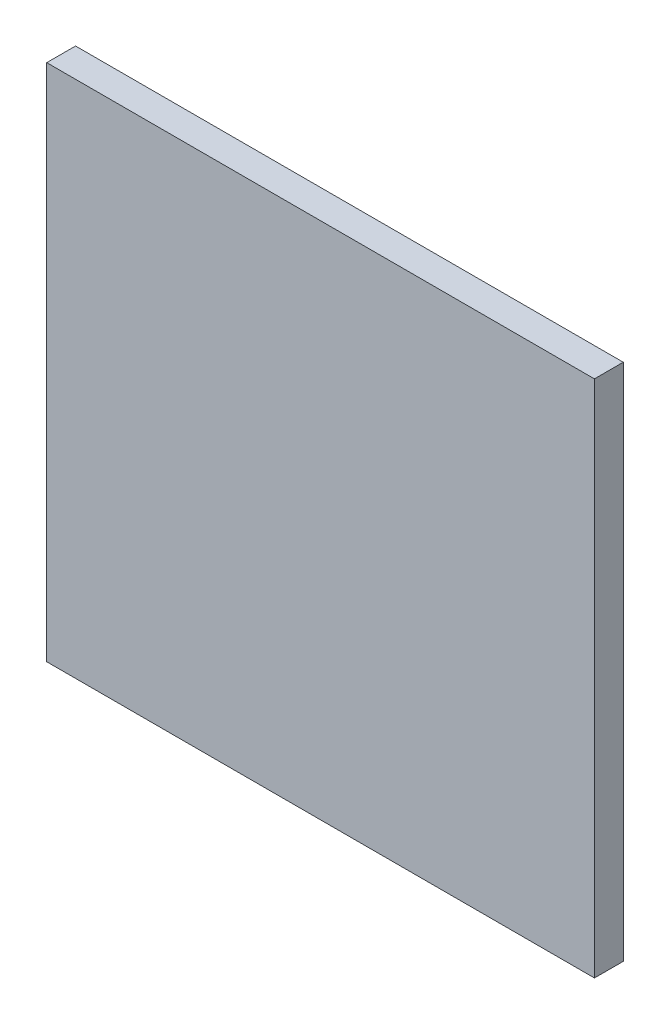
SolidWorks part; units mm, degrees
ref_plane "Спереди" through (0, 0, 0) normal (0, 0, 1) x (1, 0, 0)
ref_plane "Сверху" through (0, 0, 0) normal (0, 1, 0) x (1, 0, 0)
ref_plane "Справа" through (0, 0, 0) normal (1, 0, 0) x (0, 0, -1)
sketch "Эскиз1" plane through (0, 0, 0) normal (0, 0, 1) x (1, 0, 0)
  line L1 (0, 0) -> (3.8, 0)
  line L2 (0, 0) -> (0, -3.6)
  line L3 (0, -3.6) -> (3.8, -3.6)
  line L4 (3.8, 0) -> (3.8, -3.6)
  dimension "D1" = 3.8
  dimension "D2" = 3.6
extrude "Бобышка-Вытянуть1" add sketch "Эскиз1" along normal blind 0.2
sketch "Эскиз2" plane through (0, 0, 0) normal (0, 0, -1) x (-1, 0, 0)
  line L0 (-3.8, -1.8) -> (0, -1.8) construction
  line L1 (-0.65, -1.5) -> (-0.15, -1.5)
  line L2 (-0.65, -1.5) -> (-0.65, -2.1)
  line L3 (-0.65, -2.1) -> (-0.15, -2.1)
  line L4 (-0.15, -1.5) -> (-0.15, -2.1)
  line L5 (-3.8, -3.6) -> (-3.8, 0) construction
  line L6 (0, 0) -> (0, -3.6) construction
  line L7 (-1.9, 0) -> (-1.9, -3.6) construction
  line L8 (-3.8, 0) -> (0, 0) construction
  line L9 (0, -3.6) -> (-3.8, -3.6) construction
  line L10 (-3.8, -0.35) -> (0, -0.35) construction
  line L11 (-3.7894, -3.25) -> (0.0106, -3.25) construction
  line L12 (-2.2, -3.5) -> (-1.6, -3.5)
  line L13 (-3.7, -3) -> (-3.1, -3)
  line L14 (-3.7, -3) -> (-3.7, -3.5)
  line L15 (-3.7, -3.5) -> (-3.1, -3.5)
  line L16 (-3.1, -3) -> (-3.1, -3.5)
  line L17 (-2.2, -3.5) -> (-2.2, -3)
  line L18 (-2.2, -3) -> (-1.6, -3)
  line L19 (-1.6, -3.5) -> (-1.6, -3)
  line L20 (-3.4, 0) -> (-3.4, -3.9813) construction
  line L21 (-3.7, -0.6) -> (-3.1, -0.6)
  line L22 (-3.7, -0.6) -> (-3.7, -0.1)
  line L23 (-3.7, -0.1) -> (-3.1, -0.1)
  line L24 (-3.1, -0.6) -> (-3.1, -0.1)
  line L25 (-2.2, -0.6) -> (-1.6, -0.6)
  line L26 (-2.2, -0.6) -> (-2.2, -0.1)
  line L27 (-2.2, -0.1) -> (-1.6, -0.1)
  line L28 (-1.6, -0.6) -> (-1.6, -0.1)
  line L29 (-0.7, -3.5) -> (-0.1, -3.5)
  line L30 (-0.7, -3.5) -> (-0.7, -3)
  line L31 (-0.7, -3) -> (-0.1, -3)
  line L32 (-0.1, -3.5) -> (-0.1, -3)
  line L33 (-0.7, -0.6) -> (-0.1, -0.6)
  line L34 (-0.7, -0.6) -> (-0.7, -0.1)
  line L35 (-0.7, -0.1) -> (-0.1, -0.1)
  line L36 (-0.1, -0.6) -> (-0.1, -0.1)
  line L37 (-0.4, 0.0092) -> (-0.4, -3.5908) construction
  point P16 (-0.15, -1.8)
  point P17 (-0.4, -1.5)
  point P26 (-3.4, -3)
  point P27 (-3.1, -3.25)
  point P32 (-1.9, -3.5)
  point P33 (-1.6, -3.25)
  point P40 (-3.4, -0.6)
  point P41 (-3.1, -0.35)
  point P46 (-1.9, -0.6)
  point P47 (-1.6, -0.35)
  point P52 (-0.4, -3.5)
  point P53 (-0.1, -3.25)
  point P58 (-0.4, -0.6)
  point P59 (-0.1, -0.35)
  dimension "D1" = 0.5
  dimension "D2" = 0.6
  dimension "D3" = 1.45
  dimension "D4" = 1.45
  dimension "D5" = 0.6
  dimension "D6" = 0.5
  dimension "D7" = 1.5
  dimension "D8" = 1.5
extrude "Бобышка-Вытянуть2" add sketch "Эскиз2" along normal blind 0.006
